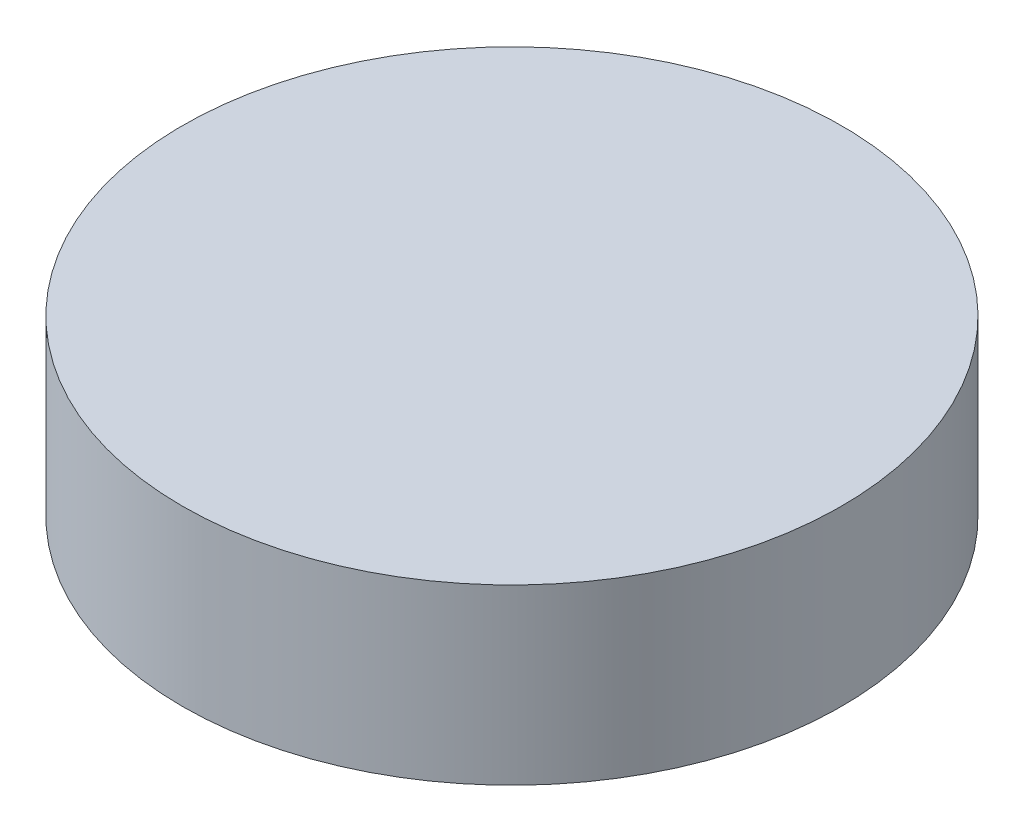
SolidWorks part; units mm, degrees
ref_plane "Front Plane" through (0, 0, 0) normal (0, 0, 1) x (1, 0, 0)
ref_plane "Top Plane" through (0, 0, 0) normal (0, 1, 0) x (1, 0, 0)
ref_plane "Right Plane" through (0, 0, 0) normal (1, 0, 0) x (0, 0, -1)
sketch "Sketch1" plane through (0, 0, 0) normal (0, 1, 0) x (1, 0, 0)
  circle A0 centre (4.9997, -4.9619) radius 12.065
  dimension "D1" = 24.13
extrude "Boss-Extrude1" add sketch "Sketch1" along normal blind 6.35
